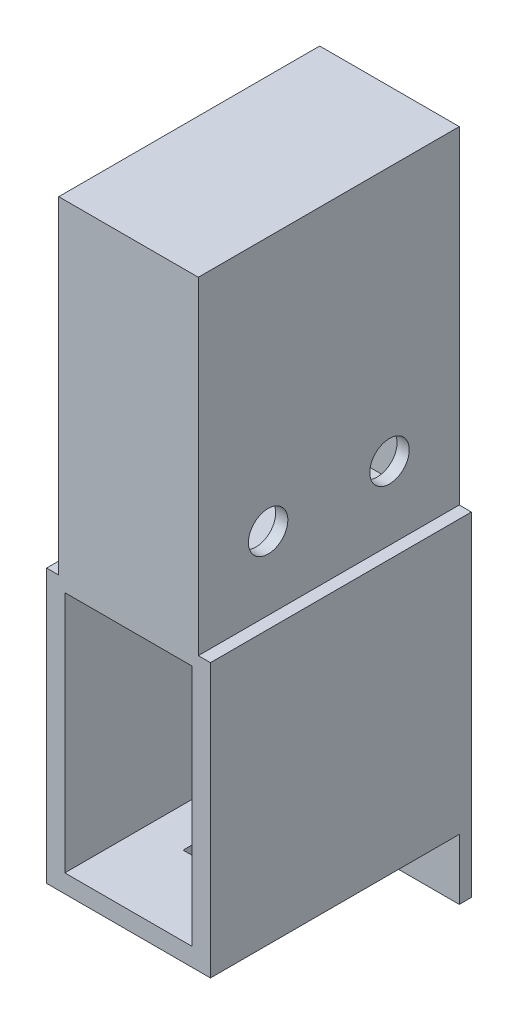
SolidWorks part; units mm, degrees
ref_plane "前视基准面" through (0, 0, 0) normal (0, 0, 1) x (1, 0, 0)
ref_plane "上视基准面" through (0, 0, 0) normal (0, 1, 0) x (1, 0, 0)
ref_plane "右视基准面" through (0, 0, 0) normal (1, 0, 0) x (0, 0, -1)
other "Configuration Table"
sketch "草图1" plane through (0, 0, 0) normal (0, 1, 0) x (1, 0, 0)
  line L1 (0, 0) -> (23, 0)
  line L2 (0, 0) -> (0, 43)
  line L3 (0, 43) -> (23, 43)
  line L4 (23, 0) -> (23, 43)
  dimension "D1" = 23
  dimension "D2" = 43
extrude "凸台-拉伸1" add sketch "草图1" along normal blind 54
sketch "草图2" plane through (0, 0, 0) normal (0, -1, 0) x (1, 0, 0)
  line L0 (21, -2) -> (2, -2)
  line L1 (2, -2) -> (2, -41)
  line L2 (2, -41) -> (21, -41)
  line L3 (21, -41) -> (21, -2)
  line L4 (0, 0) -> (0, -43)
  line L5 (0, -43) -> (23, -43)
  line L6 (23, -43) -> (23, 0)
  line L7 (23, 0) -> (0, 0)
  line L8 (0, 0) -> (0, -43)
  line L9 (0, -43) -> (23, -43)
  line L10 (23, -43) -> (23, 0)
  line L11 (23, 0) -> (0, 0)
  dimension "D1" = 0
  dimension "D2" = 2
extrude "切除-拉伸1" cut sketch "草图2" against normal blind 44 flip side to cut
sketch "草图3" plane through (0, 0, 0) normal (0, 0, 1) x (1, 0, 0)
  line L0 (0, 0) -> (23, 0) construction
  line L1 (-2, -45) -> (25, -45)
  line L2 (-2, -45) -> (-2, 0)
  line L3 (-2, 0) -> (25, 0)
  line L4 (25, -45) -> (25, 0)
  line L5 (11.5, 0) -> (11.5, -45) construction
  line L6 (-2, -22.5) -> (25, -22.5) construction
  line L7 (1, -42) -> (22, -42)
  line L8 (1, -42) -> (1, -2)
  line L9 (1, -2) -> (22, -2)
  line L10 (22, -42) -> (22, -2)
  line L11 (11.5, -2) -> (11.5, -42) construction
  line L12 (1, -22) -> (22, -22) construction
  line L13 (0, 54) -> (23, 54) construction
  point P0 (11.5, -22.5)
  point P4 (11.5, -22)
  point P19 (11.5, 54)
  dimension "D1" = 21
  dimension "D2" = 40
  dimension "D3" = 27
  dimension "D4" = 45
  dimension "D5" = 3
extrude "凸台-拉伸2" add sketch "草图3" against normal up to surface (43 mm away) up to face at (11.5, 27, -43)
sketch "草图4" plane through (0, 0, 0) normal (-1, 0, 0) x (0, 0, 1)
  line L0 (-43, 0) -> (0, 0) construction
  line L1 (-31.5, 12) -> (-11.5, 12)
  line L2 (-43, 54) -> (0, 54) construction
  line L3 (-43, 54) -> (-43, 0) construction
  circle A0 centre (-31.5, 12) radius 3.25
  circle A1 centre (-11.5, 12) radius 3.25
  point P8 (-21.5, 54)
  point P9 (-21.5, 12)
  dimension "D1" = 20
  dimension "D2" = 6.5
  dimension "D3" = 6.5
  dimension "D4" = 12
extrude "切除-拉伸2" cut sketch "草图4" against normal through all
sketch "草图5" plane through (0, 0, -43) normal (0, 0, -1) x (-1, 0, 0)
  line L3 (-25, -45) -> (2, -45) construction
  line L8 (-22, -42) -> (-1, -42) construction
  line L9 (-15.5, -42) -> (-7.5, -42)
  line L10 (-15.5, -42) -> (-15.5, -45)
  line L11 (-15.5, -45) -> (-7.5, -45)
  line L12 (-7.5, -42) -> (-7.5, -45)
  line L13 (-23, 54) -> (0, 54) construction
  point P0 (-11.5, -42)
  point P9 (-11.5, 54)
  dimension "D1" = 8
extrude "切除-拉伸3" cut sketch "草图5" against normal blind 30
sketch "草图6" plane through (0, 0, -43) normal (0, 0, -1) x (-1, 0, 0)
  line L0 (-6.5, -50) -> (-16.5, -50) construction
  line L1 (-25, -45) -> (-15.5, -45)
  line L2 (-25, -45) -> (-25, -55)
  line L3 (-25, -55) -> (-15.5, -55)
  line L4 (2, -45) -> (2, -55)
  line L5 (-7.5, -45) -> (-7.5, -48)
  line L6 (-15.5, -45) -> (-15.5, -48)
  line L7 (-7.5, -45) -> (2, -45)
  line L8 (-7.5, -55) -> (2, -55)
  line L9 (-23, 54) -> (0, 54) construction
  line L10 (2, -45) -> (2, 0) construction
  line L11 (-15.5, -48) -> (-7.5, -48)
  line L12 (-15.5, -55) -> (-7.5, -55)
  line L13 (-7.5, -42) -> (-15.5, -42) construction
  line L15 (-7.5, -55) -> (-15.5, -55)
  circle A0 centre (-16.5, -50) radius 2
  circle A1 centre (-6.5, -50) radius 2
  point P17 (-11.5, 54)
  point P18 (-11.5, -50)
  dimension "D1" = 4
  dimension "D2" = 4
  dimension "D3" = 10
  dimension "D4" = 5
  dimension "D5" = 10
  dimension "D6" = 6
extrude "凸台-拉伸3" add sketch "草图6" against normal blind 2
sketch "草图8" plane through (0, -45, 0) normal (0, -1, 0) x (1, 0, 0)
  line L0 (-17.1, -59) -> (-23.3, -59)
  line L1 (-8.6, -63.2) -> (-25.3, -63.2)
  line L2 (-8.6, -63.2) -> (-8.6, -43)
  line L3 (-8.6, -37) -> (-25.3, -37)
  line L4 (-25.3, -63.2) -> (-25.3, -37)
  line L5 (-10.6, -62.2) -> (-18.8, -62.2)
  line L6 (-10.6, -62.2) -> (-10.6, -59)
  line L7 (-10.6, -59) -> (-16.3, -59)
  line L8 (-23.3, -62.2) -> (-23.3, -60.5)
  line L10 (-16.3, -59) -> (-16.3, -60.1)
  line L11 (-16.3, -60.1) -> (-17.1, -60.1)
  line L12 (-17.1, -59) -> (-17.1, -60.1)
  line L14 (-18.8, -62.2) -> (-18.8, -61.1)
  line L15 (-18.8, -61.1) -> (-19.6, -61.1)
  line L16 (-19.6, -62.2) -> (-19.6, -61.1)
  line L17 (-23.3, -59.7) -> (-21.2, -59.7)
  line L19 (-23.3, -60.5) -> (-21.2, -60.5)
  line L20 (-21.2, -59.7) -> (-21.2, -60.5)
  line L21 (-19.6, -62.2) -> (-23.3, -62.2)
  line L22 (-23.3, -59.7) -> (-23.3, -59)
  line L24 (-2, -43) -> (0, -43) construction
  line L26 (-8.6, -37) -> (-2, -37)
  line L28 (-8.6, -43) -> (-2, -43)
  line L29 (-2, -37) -> (-2, -43)
  point P20 (-23.3, -59.35)
  point P21 (-8.6, -53.3794)
  dimension "D1" = 0.8
  dimension "D2" = 0.8
  dimension "D3" = 0.8
  dimension "D4" = 16.7
  dimension "D5" = 12.7
  dimension "D6" = 5.7
  dimension "D7" = 8.2
  dimension "D8" = 3.2
  dimension "D9" = 2
  dimension "D10" = 1.1
  dimension "D11" = 1.1
  dimension "D12" = 1
  dimension "D13" = 16
  dimension "D14" = 6
  dimension "D15" = 2.1
  dimension "D16" = 1.7
  dimension "D17" = 6.6
extrude "凸台-拉伸4" add sketch "草图8" along normal blind 10 and the other way blind 6
fillet "圆角1" radius 2 2 edges at (7.5, -48, -42) (15.5, -48, -42)
sketch "草图9" plane through (0, -39, 0) normal (0, 1, 0) x (1, 0, 0)
  line L0 (-10.6, 59) -> (-10.6, 57)
  line L1 (-10.6, 57) -> (-25.3, 57)
  line L2 (-10.6, 62.2) -> (-10.6, 63.2)
  line L7 (-8.6, 43) -> (-8.6, 63.2)
  line L8 (-8.6, 63.2) -> (-25.3, 63.2)
  line L9 (-25.3, 63.2) -> (-25.3, 37)
  line L10 (-25.3, 37) -> (-8.6, 37)
  line L11 (-8.6, 37) -> (-2, 37)
  line L12 (-2, 37) -> (-2, 43)
  line L13 (-2, 43) -> (-8.6, 43)
  line L15 (-10.6, 63.2) -> (-25.3, 63.2)
  line L16 (-23.3, 60.5) -> (-21.2, 60.5)
  line L17 (-21.2, 60.5) -> (-21.2, 59.7)
  line L18 (-21.2, 59.7) -> (-23.3, 59.7)
  line L19 (-23.3, 59.7) -> (-23.3, 59)
  line L20 (-23.3, 59) -> (-17.1, 59)
  line L21 (-17.1, 59) -> (-17.1, 60.1)
  line L22 (-17.1, 60.1) -> (-16.3, 60.1)
  line L23 (-16.3, 60.1) -> (-16.3, 59)
  line L24 (-16.3, 59) -> (-10.6, 59)
  line L25 (-10.6, 59) -> (-10.6, 62.2)
  line L26 (-10.6, 62.2) -> (-18.8, 62.2)
  line L27 (-18.8, 62.2) -> (-18.8, 61.1)
  line L28 (-18.8, 61.1) -> (-19.6, 61.1)
  line L29 (-19.6, 61.1) -> (-19.6, 62.2)
  line L30 (-19.6, 62.2) -> (-23.3, 62.2)
  line L31 (-23.3, 62.2) -> (-23.3, 60.5)
  line L32 (-23.3, 60.5) -> (-21.2, 60.5)
  line L33 (-21.2, 60.5) -> (-21.2, 59.7)
  line L34 (-21.2, 59.7) -> (-23.3, 59.7)
  line L35 (-23.3, 59.7) -> (-23.3, 59)
  line L36 (-23.3, 59) -> (-17.1, 59)
  line L37 (-17.1, 59) -> (-17.1, 60.1)
  line L38 (-17.1, 60.1) -> (-16.3, 60.1)
  line L39 (-16.3, 60.1) -> (-16.3, 59)
  line L40 (-16.3, 59) -> (-10.6, 59)
  line L41 (-10.6, 59) -> (-10.6, 62.2)
  line L42 (-10.6, 62.2) -> (-18.8, 62.2)
  line L43 (-18.8, 62.2) -> (-18.8, 61.1)
  line L44 (-18.8, 61.1) -> (-19.6, 61.1)
  line L45 (-19.6, 61.1) -> (-19.6, 62.2)
  line L46 (-19.6, 62.2) -> (-23.3, 62.2)
  line L47 (-23.3, 62.2) -> (-23.3, 60.5)
  line L48 (-25.3, 63.2) -> (-25.3, 57)
  line M25 (-16.3, 59) -> (-16.3, 60.1)
  line M26 (-16.3, 60.1) -> (-17.1, 60.1)
  line M27 (-17.1, 60.1) -> (-17.1, 59)
  line M28 (-17.1, 59) -> (-23.3, 59)
  line M29 (-23.3, 59) -> (-23.3, 59.7)
  line M30 (-23.3, 59.7) -> (-21.2, 59.7)
  line M31 (-21.2, 59.7) -> (-21.2, 60.5)
  line M32 (-21.2, 60.5) -> (-23.3, 60.5)
  line M33 (-23.3, 60.5) -> (-23.3, 62.2)
  line M34 (-23.3, 62.2) -> (-19.6, 62.2)
  line M35 (-19.6, 62.2) -> (-19.6, 61.1)
  line M36 (-19.6, 61.1) -> (-18.8, 61.1)
  line M37 (-18.8, 61.1) -> (-18.8, 62.2)
  line M38 (-18.8, 62.2) -> (-10.6, 62.2)
  line M40 (-10.6, 59) -> (-16.3, 59)
  line M42 (-8.6, 63.2) -> (-25.3, 63.2)
  line M43 (-25.3, 63.2) -> (-25.3, 37)
  dimension "D3" = 2
  dimension "D1" = 0
  dimension "D2" = 0
extrude "凸台-拉伸5" add sketch "草图9" along normal blind 30 contours L2 L1 L0 M38 M42 M43 M40 M25 M26 M27 M28 M29 M30 M31 M32 M33 M34 M35 M36 M37
